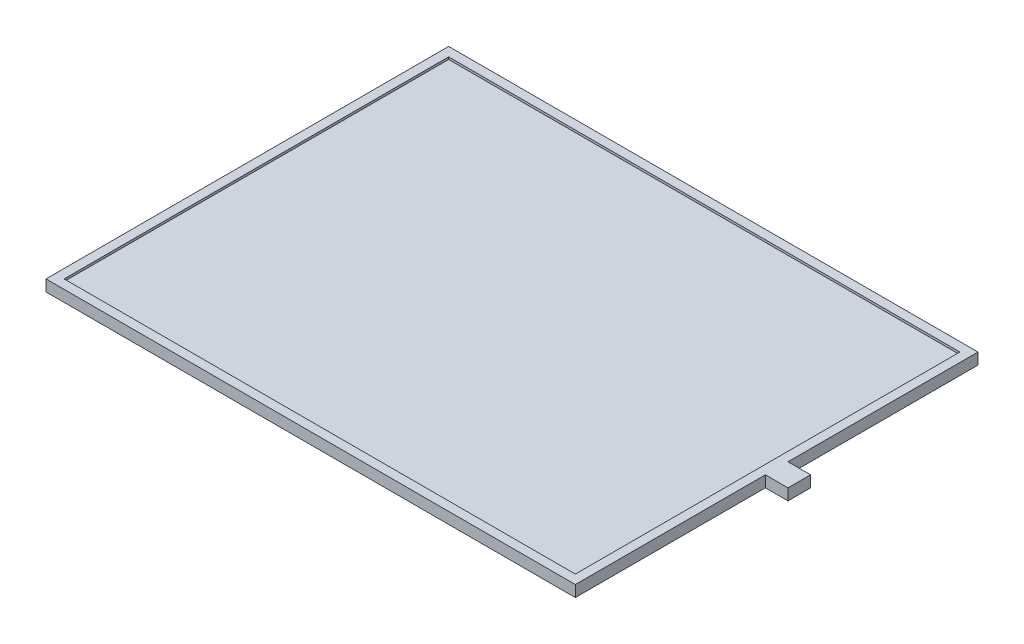
SolidWorks part; units mm, degrees
ref_plane "Front Plane" through (0, 0, 0) normal (0, 0, 1) x (1, 0, 0)
ref_plane "Top Plane" through (0, 0, 0) normal (0, 1, 0) x (1, 0, 0)
ref_plane "Right Plane" through (0, 0, 0) normal (1, 0, 0) x (0, 0, -1)
sketch "Sketch1" plane through (0, 0, 0) normal (0, 1, 0) x (1, 0, 0)
  line L0 (234, -94) -> (234, -178)
  line L1 (0, 0) -> (234, 0)
  line L2 (0, 0) -> (0, -178)
  line L3 (0, -178) -> (234, -178)
  line L4 (234, 0) -> (234, -84)
  line L5 (234, -84) -> (244, -84)
  line L7 (234, -94) -> (244, -94)
  line L8 (244, -84) -> (244, -94)
  line L10 (4, -4) -> (230, -4)
  line L11 (4, -4) -> (4, -174)
  line L12 (4, -174) -> (230, -174)
  line L13 (230, -4) -> (230, -174)
  dimension "D1" = 234
  dimension "D2" = 178
  dimension "D3" = 10
  dimension "D4" = 10
  dimension "D5" = 84
  dimension "D6" = 226
  dimension "D7" = 170
  dimension "D8" = 4
  dimension "D9" = 4
extrude "Boss-Extrude1" add sketch "Sketch1" along normal blind 5
sketch "Sketch2" plane through (0, 0, 0) normal (0, 1, 0) x (1, 0, 0)
  line L1 (4, -4) -> (230, -4)
  line L2 (4, -4) -> (4, -174)
  line L3 (4, -174) -> (230, -174)
  line L4 (230, -4) -> (230, -174)
extrude "Boss-Extrude2" add sketch "Sketch2" along normal blind 4
